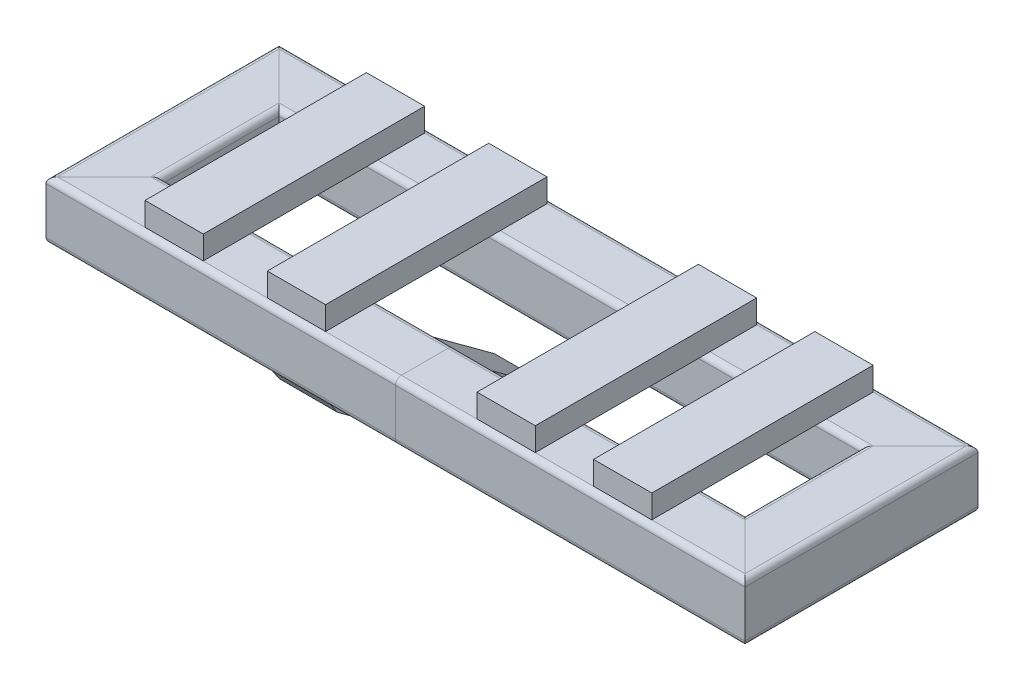
SolidWorks part; units mm, degrees
ref_plane "Front Plane" through (0, 0, 0) normal (0, 0, 1) x (1, 0, 0)
ref_plane "Top Plane" through (0, 0, 0) normal (0, 1, 0) x (1, 0, 0)
ref_plane "Right Plane" through (0, 0, 0) normal (1, 0, 0) x (0, 0, -1)
sketch "Sketch1" plane through (0, 0, 0) normal (0, 1, 0) x (1, 0, 0)
  line L1 (-300, -100) -> (300, -100)
  line L2 (-300, -100) -> (-300, 100)
  line L3 (-300, 100) -> (300, 100)
  line L4 (300, -100) -> (300, 100)
  line L5 (-300, -100) -> (300, 100) construction
  line L6 (-300, 100) -> (300, -100) construction
  point P0 (0, 0)
  dimension "D1" = 600
  dimension "D2" = 200
sketch "Sketch2" plane through (0, 0, 0) normal (1, 0, 0) x (0, 0, -1)
  line L1 (-95, 0) -> (-55, 0)
  line L2 (-100, -5) -> (-100, -45)
  line L3 (-95, -50) -> (-55, -50)
  line L4 (-50, -5) -> (-50, -45)
  arc A0 (-55, -50) -> (-50, -45) centre (-55, -45) ccw
  arc A1 (-100, -45) -> (-95, -50) centre (-95, -45) ccw
  arc A2 (-55, 0) -> (-50, -5) centre (-55, -5) cw
  arc A3 (-95, 0) -> (-100, -5) centre (-95, -5) ccw
  point P12 (-50, 0)
  point P15 (-100, 0)
  dimension "D2" = 5
  dimension "D1" = 50
sweep "Sweep1" add profiles "Sketch2" path "Sketch1"
ref_plane "Plane1" through (-90, 0, 0) normal (-1, 0, 0) x (0, 0, 1)
sketch "Sketch3" plane through (-90, 0, 0) normal (-1, 0, 0) x (0, 0, 1)
  line L0 (70, -45) -> (-170.5817, -221.8983)
  line L1 (-100, -45) -> (100, -45) construction
  line L2 (-100, -5) -> (-100, -45) construction
  line L3 (-95, 0) -> (95, 0) construction
  line L4 (100, -5) -> (100, -45) construction
  line L6 (-100, -45) -> (100, -45) construction
  point P4 (-100, -170)
  point P10 (70, -45)
  dimension "D1" = 170
  dimension "D2" = 30
ref_plane "Plane2" through (-90, -45, 70) normal (0, -0.5924, -0.8057) x (-1, 0, 0)
sketch "Sketch5" plane through (-90, -45, 70) normal (0, -0.5924, -0.8057) x (-1, 0, 0)
  line L1 (-25, -25) -> (25, -25)
  line L2 (-25, -25) -> (-25, 25)
  line L3 (-25, 25) -> (25, 25)
  line L4 (25, -25) -> (25, 25)
  line L5 (-25, -25) -> (25, 25) construction
  line L6 (-25, 25) -> (25, -25) construction
  point P0 (0, 0)
  dimension "D1" = 50
sweep "Sweep3" add profiles "Sketch5" path "Sketch3"
sketch "Sketch10" plane through (0, -50, 0) normal (0, -1, 0) x (1, 0, 0)
  line L1 (-423.2433, 180.5705) -> (423.2433, 180.5705)
  line L2 (-423.2433, 180.5705) -> (-423.2433, -180.5705)
  line L3 (-423.2433, -180.5705) -> (423.2433, -180.5705)
  line L4 (423.2433, 180.5705) -> (423.2433, -180.5705)
  line L5 (-423.2433, 180.5705) -> (423.2433, -180.5705) construction
  line L6 (-423.2433, -180.5705) -> (423.2433, 180.5705) construction
  point P0 (0, 0)
extrude "Cut-Extrude1" cut sketch "Sketch10" against normal through all
sketch "Sketch11" plane through (0, -50, 0) normal (0, -1, 0) x (1, 0, 0)
  line L0 (-115, 73.6765) -> (-115, 95)
  line L1 (-115, 95) -> (-65, 95)
  line L2 (-65, 95) -> (-65, 73.6765)
  line L3 (-65, 73.6765) -> (-115, 73.6765)
  line L4 (-295, 95) -> (0, 95) construction
  line L5 (-65, 84.8098) -> (-115, 84.8098) construction
  line L6 (-115, 84.8098) -> (-115, -155.772) construction
loft "Loft1" add profiles "Sketch11" section face at (-90, -57.5706, 79.2431) section "Sketch11"
sketch "Sketch12" plane through (0, 0, -100) normal (0, 0, -1) x (-1, 0, 0)
  line L1 (-685.4563, 512.8222) -> (685.4563, 512.8222)
  line L2 (-685.4563, 512.8222) -> (-685.4563, -512.8222)
  line L3 (-685.4563, -512.8222) -> (685.4563, -512.8222)
  line L4 (685.4563, 512.8222) -> (685.4563, -512.8222)
  line L5 (-685.4563, 512.8222) -> (685.4563, -512.8222) construction
  line L6 (-685.4563, -512.8222) -> (685.4563, 512.8222) construction
  point P0 (0, 0)
extrude "Cut-Extrude2" cut sketch "Sketch12" along normal through all
sketch "Sketch13" plane through (0, 0, 0) normal (0, 1, 0) x (1, 0, 0)
  line L0 (-295, -95) -> (0, -95) construction
  line L1 (-220, -95) -> (-170, -95)
  line L2 (-220, -95) -> (-220, 95)
  line L3 (-220, 95) -> (-170, 95)
  line L4 (-170, -95) -> (-170, 95)
  line L5 (295, 95) -> (-295, 95) construction
  line L6 (-300, 100) -> (-300, -100) construction
  line L7 (-115, -95) -> (-65, -95)
  line L8 (-115, -95) -> (-115, 95)
  line L9 (-115, 95) -> (-65, 95)
  line L10 (-65, -95) -> (-65, 95)
  line L11 (0, -95) -> (295, -95) construction
  line L12 (65, -95) -> (115, -95)
  line L13 (65, -95) -> (65, 95)
  line L14 (65, 95) -> (115, 95)
  line L15 (115, -95) -> (115, 95)
  line L16 (295, -95) -> (295, 95) construction
  line L17 (165, -95) -> (215, -95)
  line L18 (165, -95) -> (165, 95)
  line L19 (165, 95) -> (215, 95)
  line L20 (215, -95) -> (215, 95)
  dimension "D1" = 155
  dimension "D2" = 50
  dimension "D3" = 130
  dimension "D4" = 230
  dimension "D5" = 150
extrude "Boss-Extrude1" add sketch "Sketch13" along normal blind 20
